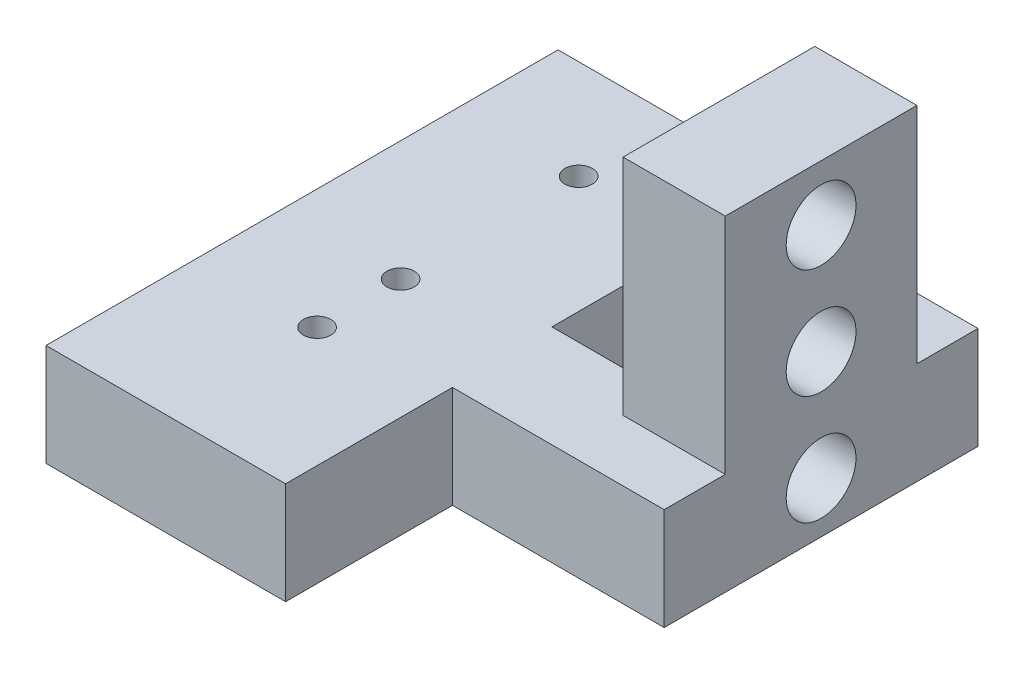
SolidWorks part; units mm, degrees
ref_plane "Front Plane" through (0, 0, 0) normal (0, 0, 1) x (1, 0, 0)
ref_plane "Top Plane" through (0, 0, 0) normal (0, 1, 0) x (1, 0, 0)
ref_plane "Right Plane" through (0, 0, 0) normal (1, 0, 0) x (0, 0, -1)
sketch "Sketch1" plane through (0, 0, 0) normal (0, 1, 0) x (1, 0, 0)
  line L0 (0, 95.561) -> (0, -103.6026) construction
  line L1 (-120.0879, 0) -> (122.2323, 0) construction
  line B0 (0, 24.3119) -> (0, -27.7936) construction
  line B1 (-27.8941, 0) -> (23.9754, 0) construction
  line B2 (8.75, 11.46) -> (24.21, 11.46)
  line B3 (8.55, 4) -> (16.75, 4)
  line B4 (8.55, 4) -> (8.55, -4)
  line B5 (8.55, -4) -> (16.75, -4)
  line B6 (16.75, 4) -> (16.75, -4)
  line B7 (8.55, 4) -> (16.75, -4) construction
  line B8 (8.55, -4) -> (16.75, 4) construction
  line B9 (-8.75, 13.75) -> (8.75, 13.75)
  line B10 (-8.75, 13.75) -> (-8.75, -23.65)
  line B11 (-8.75, -23.65) -> (8.75, -23.65)
  line B12 (8.75, 13.75) -> (8.75, 11.46)
  line B13 (-8.75, 13.75) -> (8.75, -23.65) construction
  line B14 (-8.75, -23.65) -> (8.75, 13.75) construction
  line B15 (24.21, 11.46) -> (24.21, -11.46)
  line B16 (8.75, -11.46) -> (24.21, -11.46)
  line B17 (8.75, -11.46) -> (8.75, -23.65)
  dimension "D1" = 0
  dimension "D2" = 0
sketch_block_instance "Block3-1"
sketch_block "Block3" parameters "D1"=8.2, "D2"=8, "D3"=12.65, "D4"=7.46, "D5"=7.46
extrude "Boss-Extrude1" add sketch "Sketch1" along normal blind 7.46
sketch "Sketch3" plane through (0, 7.46, 0) normal (0, 1, 0) x (1, 0, 0)
  line L0 (16.75, 0) -> (24.21, 0) construction
  line L1 (16.75, -4) -> (16.75, 4) construction
  line L2 (24.21, -11.46) -> (24.21, 11.46) construction
  line L3 (16.75, 7) -> (24.21, 7)
  line L4 (16.75, -7) -> (24.21, -7)
  line L5 (16.75, -7) -> (16.75, -4)
  line L6 (16.75, 4) -> (16.75, 7)
  line L7 (16.75, -4) -> (16.75, 4)
  line L8 (24.21, -7) -> (24.21, 7)
  dimension "D1" = 7
extrude "Boss-Extrude2" add sketch "Sketch3" along normal blind 16.34
sketch "Sketch4" plane through (16.75, 0, 0) normal (-1, 0, 0) x (0, 0, 1)
  line L0 (-4, 3.73) -> (4, 3.73) construction
  line L1 (-4, 7.46) -> (-4, 0) construction
  line L2 (4, 7.46) -> (4, 0) construction
  line L3 (0, 0) -> (0, 23.8) construction
  line L4 (4, 0) -> (-4, 0) construction
  line L5 (-7, 23.8) -> (7, 23.8) construction
  circle A0 centre (0, 3.73) radius 2.55
  circle A1 centre (0, 11.73) radius 2.55
  circle A2 centre (0, 19.73) radius 2.55
  dimension "D1" = 5.1
  dimension "D3" = 8
  dimension "D2" = 3
extrude "Cut-Extrude1" cut sketch "Sketch4" against normal through all
sketch "Sketch5" plane through (0, 0, 0) normal (0, -1, 0) x (1, 0, 0)
  line L0 (8.55, 0) -> (-8.75, 0) construction
  line L1 (8.55, -4) -> (8.55, 4) construction
  line L2 (-8.75, -13.75) -> (-8.75, 23.65) construction
  line L3 (0, -13.75) -> (0, 23.65) construction
  line L4 (8.75, -13.75) -> (-8.75, -13.75) construction
  line L5 (-8.75, 23.65) -> (8.75, 23.65) construction
  line B0 (4.9, 0) -> (-4.9, 0) construction
  line B1 (0, 18) -> (0, -18) construction
  line B2 (4.9, 14.75) -> (-5.1593, 14.75) construction
  line B3 (4.9, -14.75) -> (-5.1593, -14.75) construction
  line B4 (-2.114, 14.9661) -> (-3.6062, 0.3686)
  line B5 (-3.6062, -0.3686) -> (-2.114, -14.9661)
  line B6 (2.114, -14.9661) -> (3.6062, -0.3686)
  line B7 (2.114, 14.9661) -> (3.6062, 0.3686)
  arc B8 (2.114, 14.9661) -> (-2.114, 14.9661) centre (0, 14.75) ccw
  arc B9 (-3.6062, 0.3686) -> (-3.6062, -0.3686) centre (0, 0) ccw
  arc B10 (2.114, -14.9661) -> (-2.114, -14.9661) centre (0, -14.75) cw
  arc B11 (3.6062, -0.3686) -> (3.6062, 0.3686) centre (0, 0) ccw
  dimension "D2" = 0
  dimension "D1" = 0
sketch_block_instance "Block5-1"
sketch_block "Block5" parameters "D2"=4.25, "D3"=7.25, "D1"=14.75
extrude "Cut-Extrude2" cut sketch "Sketch5" against normal blind 1.1
sketch "Sketch6" plane through (0, 1.1, 0) normal (0, -1, 0) x (1, 0, 0)
  line L0 (0, 0) -> (-3.625, 0) construction
  line L1 (0, 0) -> (0, 16.875) construction
  line L2 (0, 6.5) -> (1.6708, 6.5) construction
  line L3 (0, 12.6) -> (1.6708, 12.6) construction
  line L4 (0, 0) -> (0, -13.75) construction
  line L5 (-2.2383, -13.75) -> (2.2383, -13.75) construction
  line L6 (0, -6.5) -> (1.6708, -6.5) construction
  arc A0 (-3.6062, 0.3686) -> (-3.6062, -0.3686) centre (0, 0) ccw construction
  arc A1 (2.114, 14.9661) -> (-2.114, 14.9661) centre (0, 14.75) ccw construction
  circle A2 centre (0, 12.6) radius 1
  circle A3 centre (0, 6.5) radius 1
  circle A4 centre (0, -6.5) radius 1
  dimension "D3" = 2
  dimension "D4" = 2
  dimension "D7" = 2
  dimension "D1" = 6.5
  dimension "D2" = 12.6
  dimension "D5" = 6.5
extrude "Cut-Extrude4" cut sketch "Sketch6" against normal up to next
